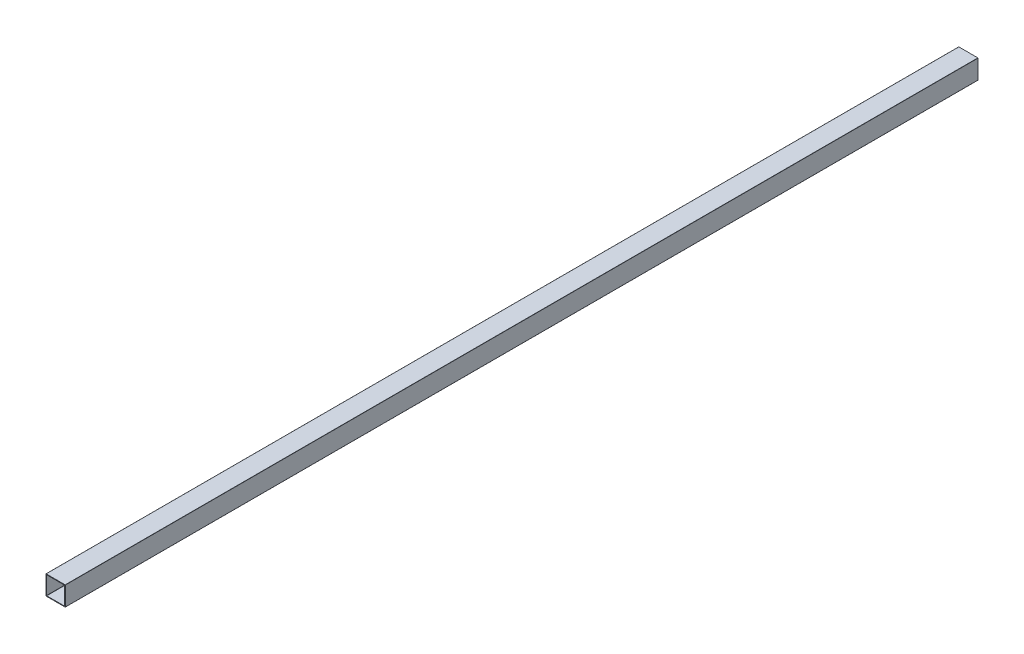
SolidWorks part; units mm, degrees
material "AISI 1035 Acero (SS)"
ref_plane "Alzado" through (0, 0, 0) normal (0, 0, 1) x (1, 0, 0)
ref_plane "Planta" through (0, 0, 0) normal (0, 1, 0) x (1, 0, 0)
ref_plane "Vista lateral" through (0, 0, 0) normal (1, 0, 0) x (0, 0, -1)
sketch "Croquis1" plane through (0, 0, 0) normal (0, 0, 1) x (1, 0, 0)
  line L0 (-59.7, -59.7) -> (-59.7, 59.7)
  line L1 (-63.5, -63.5) -> (63.5, -63.5)
  line L2 (-63.5, -63.5) -> (-63.5, 63.5)
  line L3 (-63.5, 63.5) -> (63.5, 63.5)
  line L4 (63.5, -63.5) -> (63.5, 63.5)
  line L5 (-63.5, -63.5) -> (63.5, 63.5) construction
  line L6 (-63.5, 63.5) -> (63.5, -63.5) construction
  line L7 (-59.7, 59.7) -> (59.7, 59.7)
  line L8 (59.7, -59.7) -> (59.7, 59.7)
  line L9 (-59.7, -59.7) -> (59.7, -59.7)
  point P0 (0, 0)
  dimension "D2" = 127
  dimension "D3" = 3.8
extrude "Saliente-Extruir1" add sketch "Croquis1" against normal blind 6000
fillet "Redondeo1" radius 1 8 edges at (-59.7, 59.7, -3000) (59.7, 59.7, -3000) (59.7, -59.7, -3000) (-63.5, -63.5, -3000) (-63.5, 63.5, -3000) (-59.7, -59.7, -3000) (63.5, -63.5, -3000) (63.5, 63.5, -3000)
